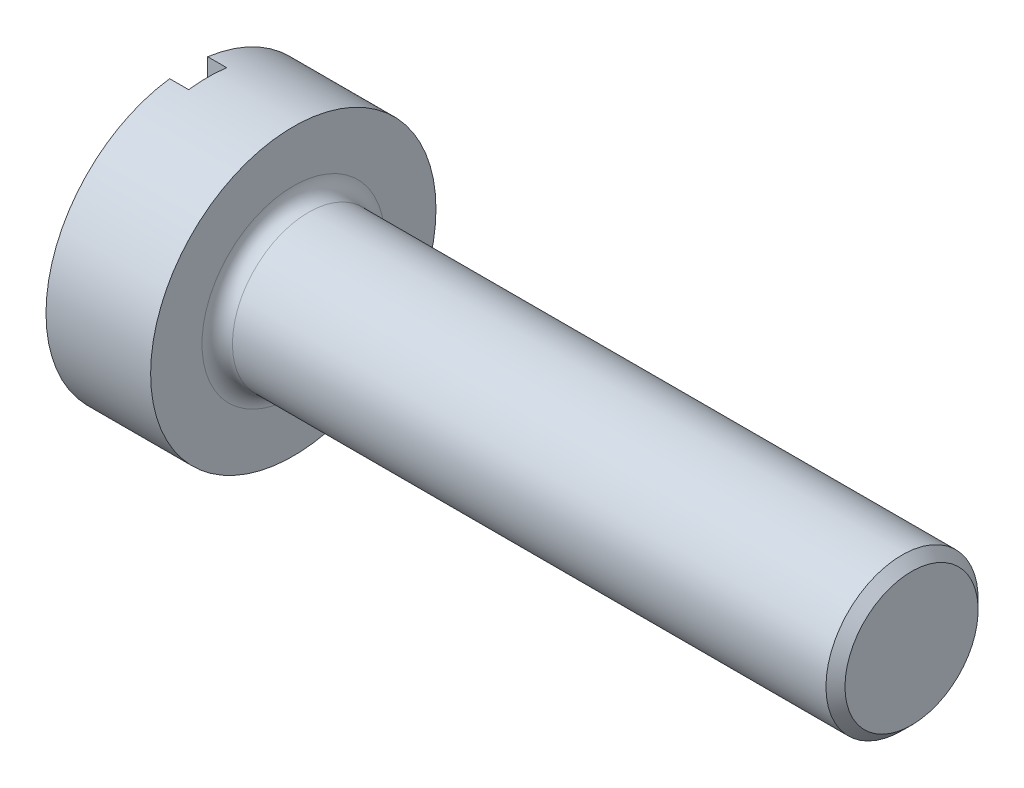
SolidWorks part; units mm, degrees
ref_plane "Front Plane" through (0, 0, 0) normal (0, 0, 1) x (1, 0, 0)
ref_plane "Top Plane" through (0, 0, 0) normal (0, 1, 0) x (1, 0, 0)
ref_plane "Right Plane" through (0, 0, 0) normal (1, 0, 0) x (0, 0, -1)
sketch "Sketch1" plane through (0, 0, 0) normal (0, 0, 1) x (1, 0, 0)
  line L0 (0, 0) -> (0, 1.5)
  line L1 (0, 1.5) -> (1.1, 1.5)
  line L2 (1.1, 1.5) -> (1.1, 0)
  line L3 (0, 0) -> (7.6, 0)
  line L4 (7.6, 0) -> (7.6, 0.8)
  line L5 (7.6, 0.8) -> (1.1, 0.8)
  dimension "D1" = 1.5
  dimension "D2" = 1.1
  dimension "D3" = 6.5
revolve "Revolve1" add sketch "Sketch1" angle 360 about L3
chamfer "Chamfer1" distance 0.1 angle 45 1 edges at (7.6, 0, 0.8)
fillet "Fillet1" radius 0.16 1 edges at (1.1, 0, 0.8)
sketch "Sketch2" plane through (0, 0, 0) normal (0, 1, 0) x (1, 0, 0)
  line L1 (0, 0) -> (0.2, 0)
  line L2 (0, 0) -> (0, 0.2)
  line L3 (0, 0.2) -> (0.2, 0.2)
  line L4 (0.2, 0) -> (0.2, 0.2)
  line L5 (0, 0) -> (0.2, 0)
  line L6 (0, 0) -> (0, -0.2)
  line L7 (0, -0.2) -> (0.2, -0.2)
  line L8 (0.2, 0) -> (0.2, -0.2)
extrude "Extrude1" cut sketch "Sketch2" against normal through all both and the other way through all contours L8 L1 L6 L7 | L1 L4 L3 L2
